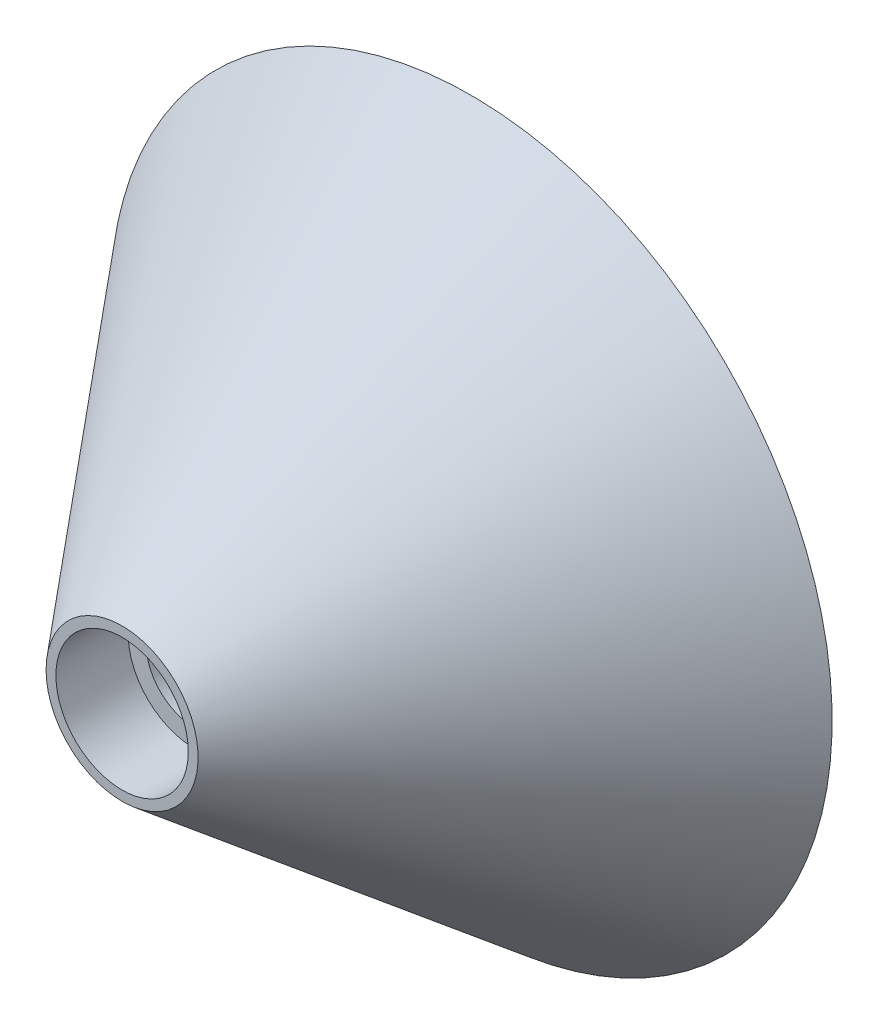
SolidWorks part; units mm, degrees
ref_plane "Přední rovina" through (0, 0, 0) normal (0, 0, 1) x (1, 0, 0)
ref_plane "Horní rovina" through (0, 0, 0) normal (0, 1, 0) x (1, 0, 0)
ref_plane "Pravá rovina" through (0, 0, 0) normal (1, 0, 0) x (0, 0, -1)
sketch "Skica1" plane through (0, 0, 0) normal (1, 0, 0) x (0, 0, -1)
  line L0 (1.2883, 5.5) -> (7.2883, 5.5)
  line L1 (-59.9598, 0) -> (80.8272, 0) construction
  line L2 (30.2883, 5.5) -> (30.2883, 30)
  line L3 (30.2883, 30) -> (1.2883, 6.3167)
  line L4 (1.2883, 6.3167) -> (1.2883, 5.5)
  line L5 (24.2883, 5.5) -> (30.2883, 5.5)
  line L7 (7.2883, 5.5) -> (7.2883, 4)
  line L8 (7.2883, 4) -> (24.2883, 4)
  line L9 (24.2883, 5.5) -> (24.2883, 4)
  dimension "D1" = 5.5
  dimension "D2" = 30
  dimension "D3" = 6
  dimension "D4" = 6
  dimension "D5" = 4
revolve "Rotovat1" add sketch "Skica1" angle 360 about L1
